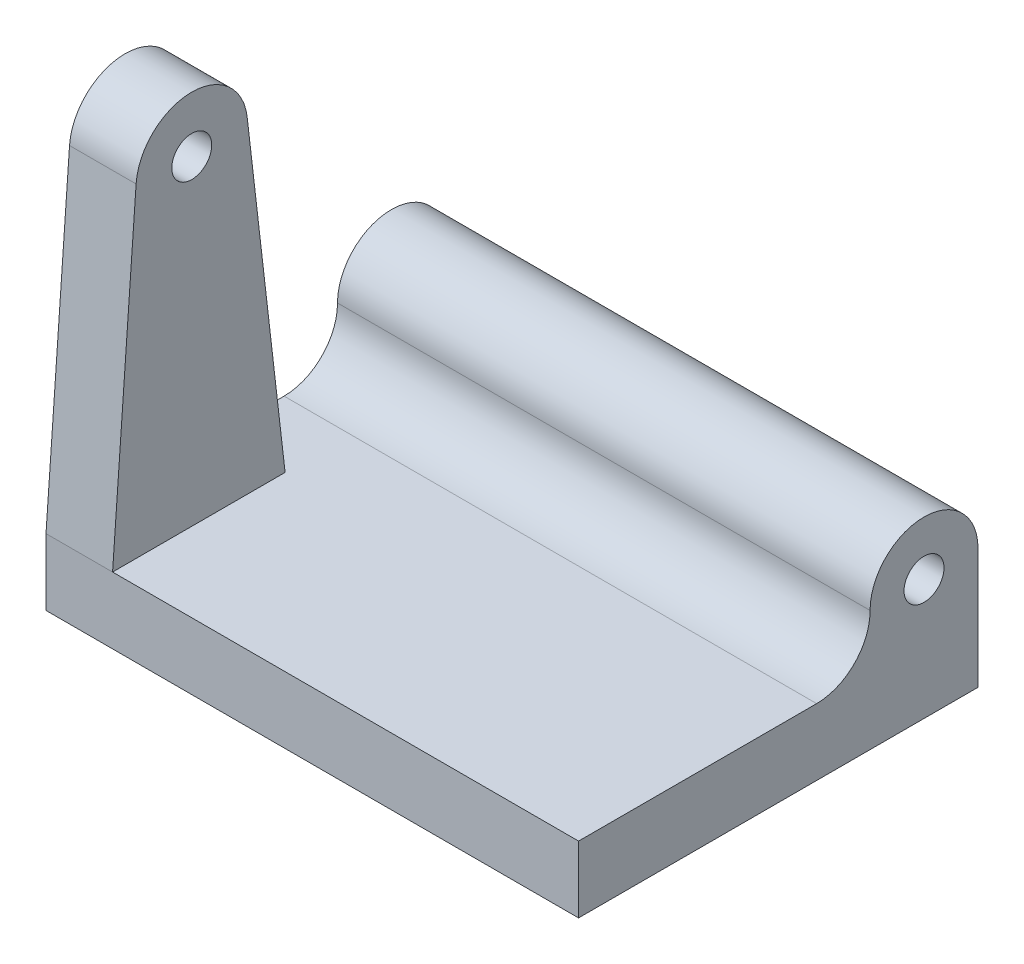
SolidWorks part; units mm, degrees
ref_plane "Front Plane" through (0, 0, 0) normal (0, 0, 1) x (1, 0, 0)
ref_plane "Top Plane" through (0, 0, 0) normal (0, 1, 0) x (1, 0, 0)
ref_plane "Right Plane" through (0, 0, 0) normal (1, 0, 0) x (0, 0, -1)
sketch "Sketch1" plane through (0, 0, 0) normal (0, 1, 0) x (1, 0, 0)
  line L1 (0, 0) -> (40, 0)
  line L2 (0, 0) -> (0, -30)
  line L3 (0, -30) -> (40, -30)
  line L4 (40, 0) -> (40, -30)
  dimension "D1" = 30
  dimension "D2" = 40
extrude "Boss-Extrude1" add sketch "Sketch1" along normal blind 5
sketch "Sketch2" plane through (0, 0, 0) normal (-1, 0, 0) x (0, 0, 1)
  line L0 (0, 9.0545) -> (0, 5)
  line L1 (0, 5) -> (12.1169, 5)
  circle A0 centre (4.0533, 9.0545) radius 1.5
  arc A1 (8.1066, 9.0323) -> (0, 9.0545) centre (4.0533, 9.0545) ccw
  arc A2 (8.1067, 9.0545) -> (12.1169, 5) centre (12.1391, 9.0324) ccw
  line M3 (30, 5) -> (0, 5)
  dimension "D1" = 3
extrude "Boss-Extrude2" add sketch "Sketch2" against normal blind 40 contours A2 A1 L0 A0 M3
sketch "Sketch3" plane through (40, 0, 0) normal (1, 0, 0) x (0, 0, -1)
  line L0 (-30, 5) -> (-28.2327, 29.3577)
  line L1 (-19.891, 29.5378) -> (-17.0415, 5)
  line L2 (-30, 5) -> (-12.1169, 5) construction
  line L3 (-30, 5) -> (-17.0415, 5)
  circle A0 centre (-24.0533, 29.0545) radius 1.5
  arc A1 (-19.891, 29.5378) -> (-28.2327, 29.3577) centre (-24.0533, 29.0545) ccw
  point P0 (-4.0533, 9.0545)
  point P1 (-24.0533, 29.0545)
  dimension "D3" = 3
  dimension "D1" = 20
  dimension "D2" = 20
sketch "Sketch4" plane through (0, 0, 0) normal (-1, 0, 0) x (0, 0, 1)
  line L3 (30, 5) -> (28.2327, 29.3577)
  line L4 (19.891, 29.5378) -> (17.0415, 5)
  line L5 (17.0415, 5) -> (30, 5)
  line L6 (30, 5) -> (28.2327, 29.3577)
  line L7 (19.891, 29.5378) -> (17.0415, 5)
  line L8 (17.0415, 5) -> (30, 5)
  circle A1 centre (24.0533, 29.0545) radius 1.5
  circle A2 centre (24.0533, 29.0545) radius 1.5
  arc A3 (28.2327, 29.3577) -> (19.891, 29.5378) centre (24.0533, 29.0545) ccw
  arc A4 (28.2327, 29.3577) -> (19.891, 29.5378) centre (24.0533, 29.0545) ccw
  dimension "D1" = 0
  dimension "D2" = 0
extrude "Boss-Extrude4" add sketch "Sketch4" against normal blind 5
